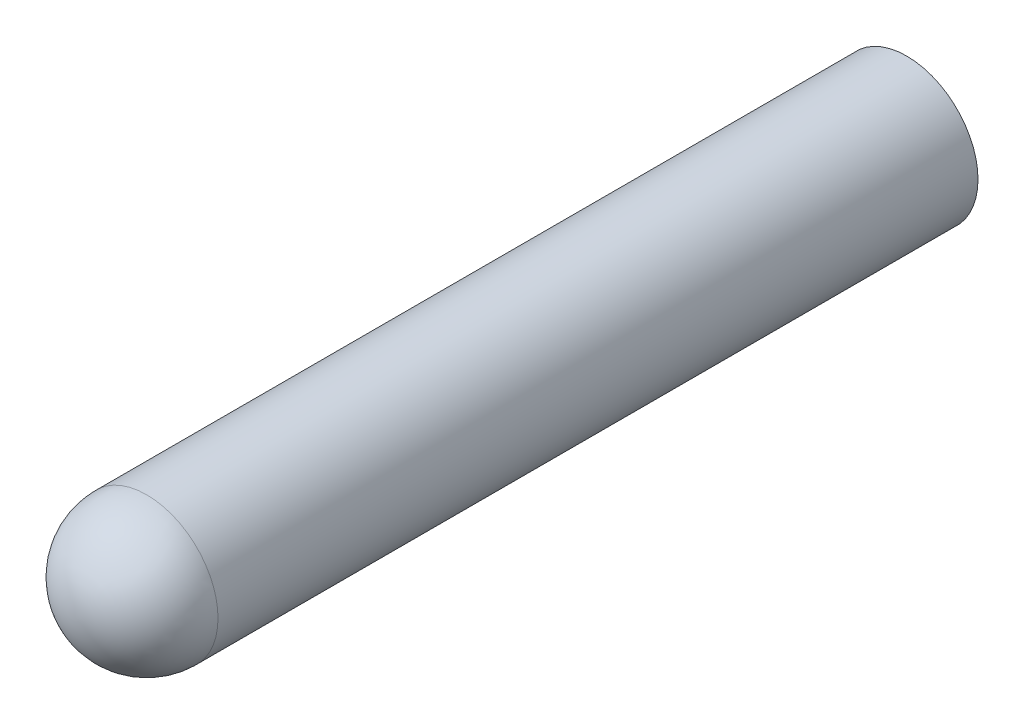
SolidWorks part; units mm, degrees
ref_plane "Front Plane" through (0, 0, 0) normal (0, 0, 1) x (1, 0, 0)
ref_plane "Top Plane" through (0, 0, 0) normal (0, 1, 0) x (1, 0, 0)
ref_plane "Right Plane" through (0, 0, 0) normal (1, 0, 0) x (0, 0, -1)
sketch "Croquis2" plane through (0, 0, 0) normal (0, 0, 1) x (1, 0, 0)
  circle A0 centre (407.6478, 485.2031) radius 3
  dimension "D1" = 6
extrude "Saliente-Extruir1" add sketch "Croquis2" along normal blind 35
fillet "Redondeo1" radius 3 1 edges at (410.6478, 485.2031, 35)
sketch "Croquis3" plane through (0, 0, 0) normal (0, 0, -1) x (-1, 0, 0)
  circle A0 centre (-407.6478, 485.2031) radius 1.5
  dimension "D1" = 3
extrude "Cortar-Extruir1" cut sketch "Croquis3" against normal blind 5
